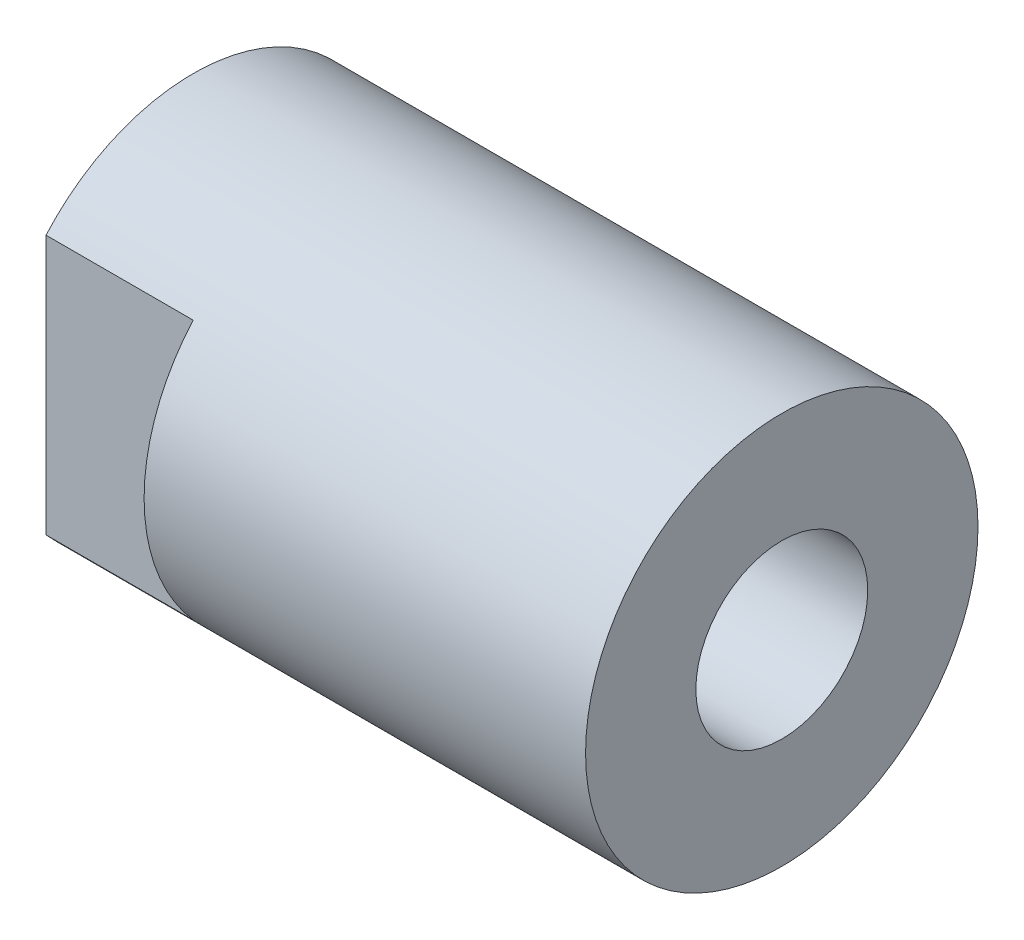
SolidWorks part; units mm, degrees
ref_plane "Front Plane" through (0, 0, 0) normal (0, 0, 1) x (1, 0, 0)
ref_plane "Top Plane" through (0, 0, 0) normal (0, 1, 0) x (1, 0, 0)
ref_plane "Right Plane" through (0, 0, 0) normal (1, 0, 0) x (0, 0, -1)
sketch "Sketch1" plane through (0, 0, 0) normal (0, 0, 1) x (1, 0, 0)
  line L0 (0, 1.796) -> (1.9632, 1.27)
  line L2 (0, 1.796) -> (0, 12.7)
  line L3 (0, 12.7) -> (38.1, 12.7)
  line L4 (38.1, 5.5626) -> (38.1, 12.7)
  line L5 (1.9632, 1.27) -> (5.2054, 1.27)
  line L6 (5.2054, 1.27) -> (6.35, 3.175)
  line L7 (6.35, 3.175) -> (12.7, 3.175)
  line L8 (0, 0) -> (86.5476, 0) construction
  line L9 (12.7, 3.175) -> (12.7, 5.5626)
  line L10 (12.7, 5.5626) -> (38.1, 5.5626)
  dimension "D1" = 38.1
  dimension "D2" = 5.5626
  dimension "D3" = 12.7
  dimension "D4" = 15
  dimension "D5" = 59
  dimension "D6" = 31.75
  dimension "D7" = 3.175
  dimension "D8" = 1.9632
  dimension "D9" = 1.27
  dimension "D10" = 25.4
revolve "Revolve1" add sketch "Sketch1" angle 360 about L8
sketch "Sketch2" plane through (0, 0, 0) normal (-1, 0, 0) x (0, 0, 1)
  line L0 (-9.525, -8.4003) -> (-9.525, 8.4003)
  line L1 (9.525, 8.4003) -> (9.525, -8.4003)
  circle A0 centre (0, 0) radius 12.7
  circle M5 centre (0, 0) radius 12.7
  dimension "D1" = 25.4
  dimension "D2" = 9.525
  dimension "D3" = 9.525
extrude "Cut-Extrude1" cut sketch "Sketch2" against normal blind 9.525 contours L0 M5 | L1 M5
